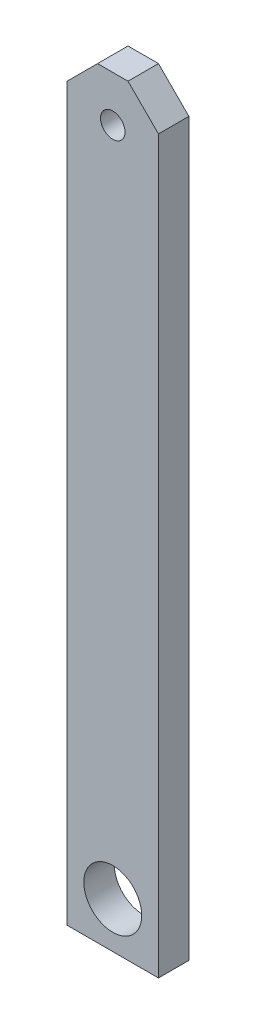
SolidWorks part; units mm, degrees
material "6061 Alloy"
ref_plane "Front" through (0, 0, 0) normal (0, 0, 1) x (1, 0, 0)
ref_plane "Top" through (0, 0, 0) normal (0, 1, 0) x (1, 0, 0)
ref_plane "Right" through (0, 0, 0) normal (1, 0, 0) x (0, 0, -1)
sketch "Sketch1" plane through (0, 0, 0) normal (0, 0, 1) x (1, 0, 0)
  line L1 (0, 0) -> (19.05, 0)
  line L2 (0, 0) -> (0, 158.75)
  line L3 (0, 158.75) -> (19.05, 158.75)
  line L4 (19.05, 0) -> (19.05, 158.75)
  dimension "D1" = 19.05
  dimension "D2" = 158.75
extrude "Boss-Extrude1" add sketch "Sketch1" along normal blind 6.35
hole_wizard "1/4-20 Tapped Hole1" positions "Sketch2" profile "Sketch3" tap size "1/4-20" standard "ANSI Inch" end condition up to next
sketch "Sketch2" plane through (0, 0, 6.35) normal (0, 0, 1) x (1, 0, 0)
  line L0 (9.525, 149.225) -> (19.05, 149.225) construction
  line L1 (19.05, 0) -> (19.05, 158.75) construction
  line L3 (9.525, 149.225) -> (9.525, 158.75) construction
  line L4 (19.05, 158.75) -> (0, 158.75) construction
  point P0 (9.525, 149.225)
sketch "Sketch3" plane through (9.525, 149.225, 6.35) normal (1, 0, 0) x (0, -1, 0)
  line L0 (0, 0) -> (0, 6.35)
  line L1 (0, 6.35) -> (2.5527, 6.35)
  line L2 (2.5527, 6.35) -> (2.5527, 0)
  line L5 (2.5527, 0) -> (0, 0)
  line L11 (0, -6.35) -> (0, 107.95) construction
  dimension "Thru Tap Drill Dia." = 5.1054
  dimension "Thru Tap Drill Depth" = 6.35
cosmetic thread "Hole Thread1"
hole_wizard "1/4 (0.475) Diameter Hole1" positions "Sketch4" profile "Sketch5" hole size "1/4" standard "ANSI Inch" end condition up to next
sketch "Sketch4" plane through (0, 0, 6.35) normal (0, 0, 1) x (1, 0, 0)
  line L0 (9.525, 0) -> (9.525, 9.525) construction
  line L1 (50, 0) -> (-50, 0) construction
  line L3 (0, 0) -> (19.05, 0) construction
  circle A0 centre (9.525, 149.225) radius 2.5527 construction
  point P0 (9.525, 9.525)
  dimension "D1" = 139.7
sketch "Sketch5" plane through (9.525, 9.525, 6.35) normal (1, 0, 0) x (0, -1, 0)
  line L0 (0, 0) -> (0, 6.35)
  line L1 (0, 6.35) -> (6.0325, 6.35)
  line L2 (6.0325, 6.35) -> (6.0325, 0)
  line L5 (6.0325, 0) -> (0, 0)
  line L11 (0, -6.35) -> (0, 107.95) construction
  dimension "Thru Hole Dia." = 12.065
  dimension "Thru Hole Depth" = 6.35
chamfer "Chamfer1" distance 6.35 angle 45 2 edges at (0, 158.75, 3.175) (19.05, 158.75, 3.175)
